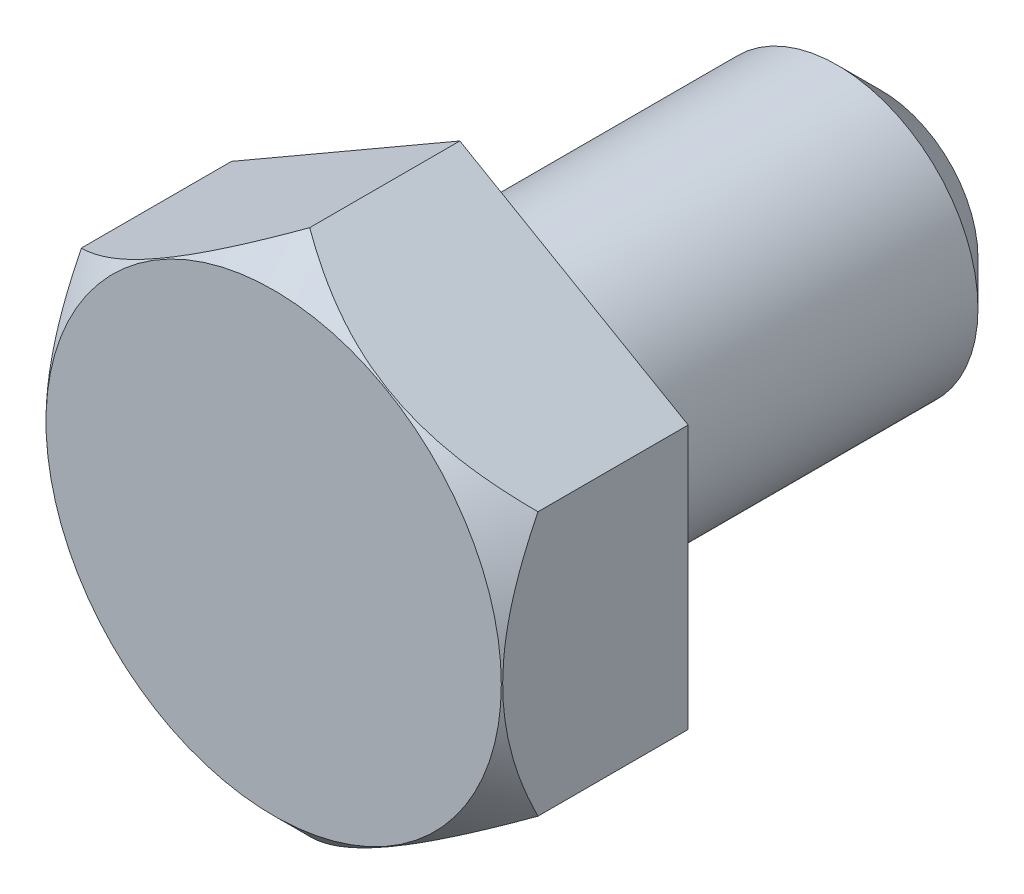
SolidWorks part; units mm, degrees
ref_plane "Спереди" through (0, 0, 0) normal (0, 0, 1) x (1, 0, 0)
ref_plane "Сверху" through (0, 0, 0) normal (0, 1, 0) x (1, 0, 0)
ref_plane "Справа" through (0, 0, 0) normal (1, 0, 0) x (0, 0, -1)
sketch "Эскиз1" plane through (0, 0, 0) normal (0, 0, 1) x (1, 0, 0)
  line L0 (0, 4.93) -> (0, -5.4719) construction
  line L1 (-5.0323, 0) -> (5.1026, 0) construction
  line L3 (0, 7.5056) -> (-6.5, 3.7528)
  line L4 (-6.5, 3.7528) -> (-6.5, -3.7528)
  line L5 (-6.5, -3.7528) -> (0, -7.5056)
  line L6 (0, -7.5056) -> (6.5, -3.7528)
  line L7 (6.5, -3.7528) -> (6.5, 3.7528)
  line L8 (6.5, 3.7528) -> (0, 7.5056)
  circle A0 centre (0, 0) radius 6.5 construction
extrude "Вытянуть1" add sketch "Эскиз1" along normal blind 5.3
sketch "Эскиз2" plane through (0, 0, 0) normal (0, 0, -1) x (-1, 0, 0)
  circle A0 centre (0, 0) radius 4
extrude "Вытянуть2" add sketch "Эскиз2" along normal blind 12
ref_axis "Ось4" through (0, 0, 0.4653) along (0, 0, -1)
sketch "Эскиз15" plane through (0, 0, 0) normal (1, 0, 0) x (0, 0, -1)
  line L0 (-5.3, 7.5056) -> (-5.3, 6.4806)
  line L1 (-5.3, 3.7528) -> (-5.3, 7.5056) construction
  line L2 (-5.3, 6.4806) -> (-4.275, 7.5056)
  line L3 (-5.3, 7.5056) -> (0, 7.5056) construction
  line L4 (-4.275, 7.5056) -> (-5.3, 7.5056)
revolve "Вырез-Повернуть1" cut sketch "Эскиз15" angle 360 about axis through (0, 0, 0.4653) along (0, 0, -1)
ref_plane "Плоскость1" through (0, 0, 0) normal (0, -1, 0) x (1, 0, 0)
chamfer "Фаска1" distance 1.25 angle 45 1 edges at (-4, 0, -12)
